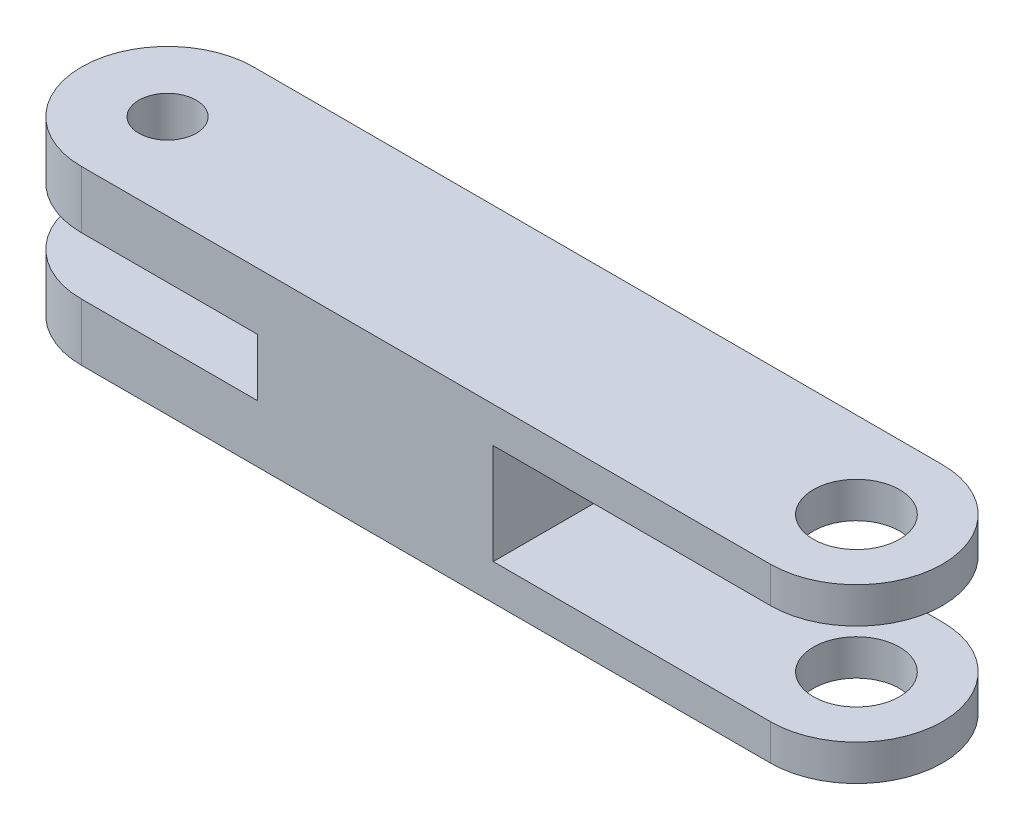
SolidWorks part; units mm, degrees
ref_plane "前视基准面" through (0, 0, 0) normal (0, 0, 1) x (1, 0, 0)
ref_plane "上视基准面" through (0, 0, 0) normal (0, 1, 0) x (1, 0, 0)
ref_plane "右视基准面" through (0, 0, 0) normal (1, 0, 0) x (0, 0, -1)
other "Configuration Table"
sketch "草图1" plane through (0, 0, 0) normal (0, 1, 0) x (1, 0, 0)
  line L0 (0, 0) -> (1, 0) construction
  line L1 (22.5, 0) -> (24, 0) construction
  line L2 (0, 3) -> (24, 3)
  line L3 (0, -3) -> (24, -3)
  arc A0 (0, 3) -> (0, -3) centre (0, 0) ccw
  arc A1 (24, -3) -> (24, 3) centre (24, 0) ccw
  circle A2 centre (24, 0) radius 1.5
  circle A3 centre (0, 0) radius 1
  point P3 (20, 0)
  dimension "D2" = 3
  dimension "D3" = 3
  dimension "D4" = 2
  dimension "D1" = 24
extrude "凸台-拉伸1" add sketch "草图1" along normal mid plane 6
sketch "草图6" plane through (0, 0, 0) normal (0, 1, 0) x (1, 0, 0)
  line L0 (14.3461, 7.8432) -> (14.3461, -3.762)
  line L1 (14.3461, -3.762) -> (45.8575, -3.762)
  line L2 (45.8575, -3.762) -> (45.8575, 7.8432)
  line L3 (45.8575, 7.8432) -> (14.3461, 7.8432)
extrude "切除-拉伸2" cut sketch "草图6" against normal mid plane 3.5
sketch "草图7" plane through (0, 0, 0) normal (0, 1, 0) x (1, 0, 0)
  line L0 (6.139, 5.0358) -> (6.139, -4.6141)
  line L1 (6.139, -4.6141) -> (-6.5212, -4.6141)
  line L2 (-6.5212, -4.6141) -> (-6.5212, 5.0358)
  line L3 (-6.5212, 5.0358) -> (6.139, 5.0358)
extrude "切除-拉伸3" cut sketch "草图7" against normal mid plane 2
